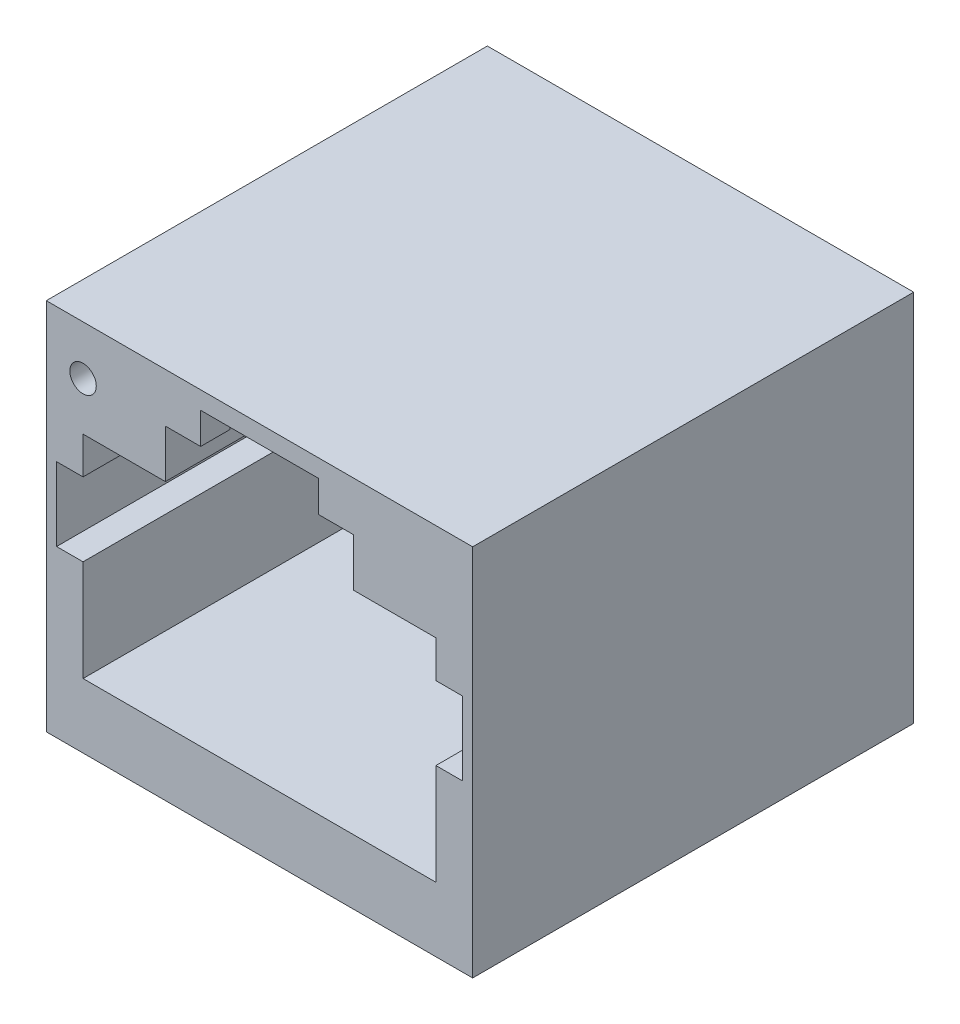
SolidWorks part; units mm, degrees
ref_plane "Front Plane" through (0, 0, 0) normal (0, 0, 1) x (1, 0, 0)
ref_plane "Top Plane" through (0, 0, 0) normal (0, 1, 0) x (1, 0, 0)
ref_plane "Right Plane" through (0, 0, 0) normal (1, 0, 0) x (0, 0, -1)
sketch "Sketch2" plane through (0, 0, 0) normal (0, 1, 0) x (1, 0, 0)
  line L1 (-7.25, -7.5) -> (7.25, -7.5)
  line L2 (-7.25, -7.5) -> (-7.25, 7.5)
  line L3 (-7.25, 7.5) -> (7.25, 7.5)
  line L4 (7.25, -7.5) -> (7.25, 7.5)
  line L5 (-7.25, -7.5) -> (7.25, 7.5) construction
  line L6 (-7.25, 7.5) -> (7.25, -7.5) construction
  point P0 (0, 0)
  dimension "D1" = 14.5
  dimension "D2" = 15
extrude "Outline extrusion" add sketch "Sketch2" along normal blind 12.7
sketch "Sketch3" plane through (0, 0, 7.5) normal (0, 0, 1) x (1, 0, 0)
  line L0 (-7.25, 12.7) -> (7.25, 12.7) construction
  line L1 (-6, 9.3952) -> (6, 9.3952)
  line L2 (-6, 9.3952) -> (-6, 2.1952)
  line L3 (-6, 2.1952) -> (6, 2.1952)
  line L4 (6, 9.3952) -> (6, 2.1952)
  line L5 (-3.2, 9.3952) -> (3.2, 9.3952)
  line L6 (-3.2, 9.3952) -> (-3.2, 11.0305)
  line L7 (-3.2, 11.0305) -> (3.2, 11.0305)
  line L8 (3.2, 9.3952) -> (3.2, 11.0305)
  line L9 (-2, 11.0305) -> (2, 11.0305)
  line L10 (-2, 11.0305) -> (-2, 12.0952)
  line L11 (-2, 12.0952) -> (2, 12.0952)
  line L12 (2, 11.0305) -> (2, 12.0952)
  line L13 (-6, 8.1332) -> (-6.9, 8.1332)
  line L14 (-6, 8.1332) -> (-6, 5.6332)
  line L15 (-6, 5.6332) -> (-6.9, 5.6332)
  line L16 (-6.9, 8.1332) -> (-6.9, 5.6332)
  line L17 (6, 8.1332) -> (6.9, 8.1332)
  line L18 (6, 8.1332) -> (6, 5.6332)
  line L19 (6, 5.6332) -> (6.9, 5.6332)
  line L20 (6.9, 8.1332) -> (6.9, 5.6332)
  point P22 (0, 12.7)
  point P23 (0, 12.0952)
  point P24 (0, 11.0305)
  point P25 (0, 9.3952)
  dimension "D1" = 0
  dimension "D2" = 0
  dimension "D3" = 0
  dimension "D4" = 12
  dimension "D5" = 7.2
  dimension "D6" = 2.5
  dimension "D7" = 2.5
  dimension "D8" = 0.9
  dimension "D9" = 0.9
  dimension "D10" = 4
  dimension "D11" = 6.4
  dimension "D12" = 9.9
  dimension "D13" = 0.6048
extrude "Cut-Extrude1" cut sketch "Sketch3" against normal blind 14 contours L4 L1 L2 L3 | L1 L8 L7 L6 | L7 L12 L11 L10 | L20 L17 L4 L19 | L16 L15 L14 L13
sketch "Sketch5" plane through (0, 0, 7.5) normal (0, 0, 1) x (1, 0, 0)
  circle A0 centre (-6, 11.0305) radius 0.45
  dimension "D2" = 0.9
  dimension "D1" = 0
extrude "Cut-Extrude2" cut sketch "Sketch5" against normal blind 14
sketch "Sketch6" plane through (0, 0, -6.5) normal (0, 0, 1) x (1, 0, 0)
  line L0 (-2, 11.9952) -> (2, 11.9952)
  line L1 (-2, 11.0305) -> (-2, 12.0952) construction
  line L2 (2, 11.0305) -> (2, 12.0952) construction
  line L3 (-2, 12.0952) -> (2, 12.0952) construction
  line M6 (2, 11.0305) -> (2, 12.0952)
  line M7 (2, 12.0952) -> (-2, 12.0952)
  line M8 (-2, 12.0952) -> (-2, 11.0305)
  dimension "D1" = 0.1
extrude "Boss-Extrude1" add sketch "Sketch6" along normal blind 11.5 contours L0 M8 M6 M7
sketch "Sketch7" plane through (0, 0, -6.5) normal (0, 0, 1) x (1, 0, 0)
  line L1 (-3.2, 11.0305) -> (-2, 11.0305)
  line L2 (-3.2, 11.0305) -> (-3.2, 11.9952)
  line L3 (-3.2, 11.9952) -> (-2, 11.9952)
  line L4 (-2, 11.0305) -> (-2, 11.9952)
  line L5 (3.2, 11.0305) -> (2, 11.0305)
  line L6 (3.2, 11.0305) -> (3.2, 11.9952)
  line L7 (3.2, 11.9952) -> (2, 11.9952)
  line L8 (2, 11.0305) -> (2, 11.9952)
extrude "Cut-Extrude3" cut sketch "Sketch7" along normal blind 13
